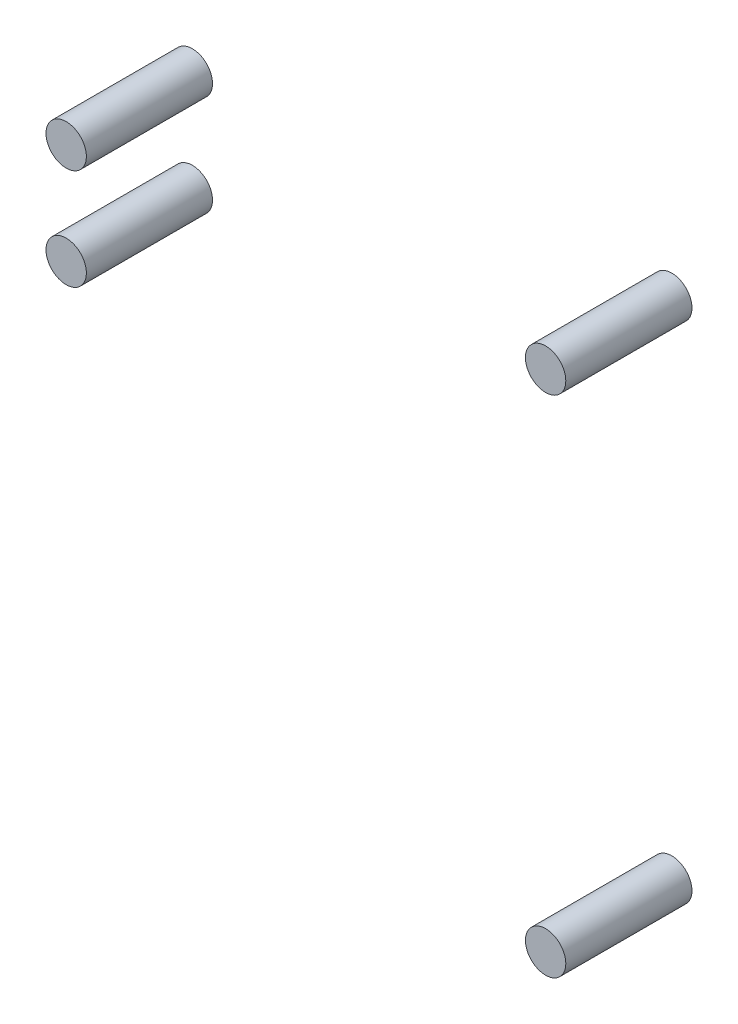
SolidWorks part; units mm, degrees
ref_plane "FP" through (0, 0, 0) normal (0, 0, 1) x (1, 0, 0)
ref_plane "TP" through (0, 0, 0) normal (0, 1, 0) x (1, 0, 0)
ref_plane "RP" through (0, 0, 0) normal (1, 0, 0) x (0, 0, -1)
sketch "Sketch1" plane through (0, 0, 0) normal (0, 0, 1) x (1, 0, 0)
  circle A0 centre (27, 8.5) radius 2 construction
  circle A1 centre (27, 18.5) radius 2 construction
  circle A2 centre (74.5, 23) radius 2 construction
  circle A3 centre (74.5, -27) radius 2 construction
  circle A4 centre (27, 8.5) radius 2
  circle A5 centre (27, 18.5) radius 2
  circle A6 centre (74.5, 23) radius 2
  circle A7 centre (74.5, -27) radius 2
extrude "Boss-Extrude1" add sketch "Sketch1" against normal blind 7.5 and the other way blind 5
